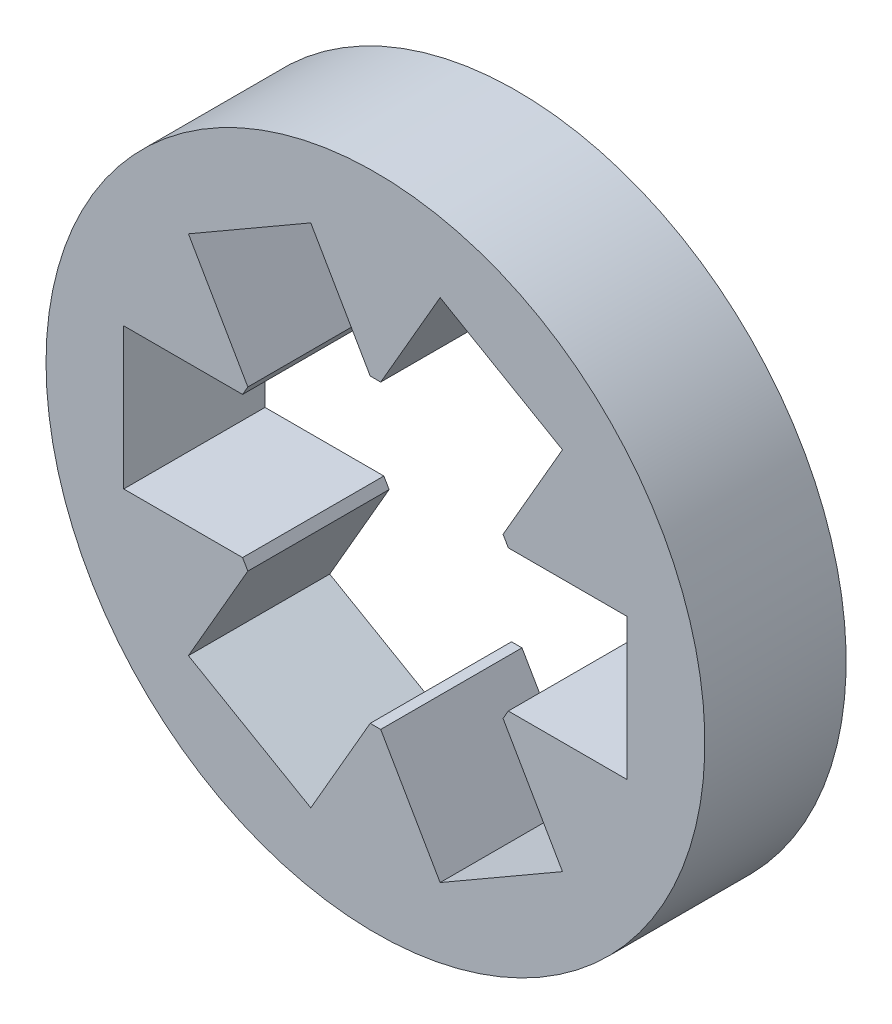
SolidWorks part; units mm, degrees
ref_plane "Front Plane" through (0, 0, 0) normal (0, 0, 1) x (1, 0, 0)
ref_plane "Top Plane" through (0, 0, 0) normal (0, 1, 0) x (1, 0, 0)
ref_plane "Right Plane" through (0, 0, 0) normal (1, 0, 0) x (0, 0, -1)
sketch "Sketch1" plane through (0, 0, 0) normal (0, 0, 1) x (1, 0, 0)
  line L0 (110.2077, 0) -> (110.2077, -1.524)
  line L1 (110.2077, -1.524) -> (108.9259, -1.524)
  line L2 (108.9259, -1.524) -> (108.8691, -1.6222)
  line L3 (108.8691, -1.6222) -> (109.51, -2.7323)
  line L4 (109.51, -2.7323) -> (108.1902, -3.4943)
  line L5 (108.1902, -3.4943) -> (107.5493, -2.3842)
  line L6 (107.5493, -2.3842) -> (107.4359, -2.3842)
  line L7 (107.4359, -2.3842) -> (106.795, -3.4943)
  line L8 (106.795, -3.4943) -> (105.4751, -2.7323)
  line L9 (105.4751, -2.7323) -> (106.116, -1.6222)
  line L10 (106.116, -1.6222) -> (106.0593, -1.524)
  line L11 (106.0593, -1.524) -> (104.7775, -1.524)
  line L12 (104.7775, -1.524) -> (104.7775, 0)
  line L13 (104.7775, 0) -> (106.0593, 0)
  line L14 (106.0593, 0) -> (106.116, 0.0982)
  line L15 (106.116, 0.0982) -> (105.4751, 1.2083)
  line L16 (105.4751, 1.2083) -> (106.795, 1.9703)
  line L17 (106.795, 1.9703) -> (107.4359, 0.8602)
  line L18 (107.4359, 0.8602) -> (107.5493, 0.8602)
  line L19 (107.5493, 0.8602) -> (108.1902, 1.9703)
  line L20 (108.1902, 1.9703) -> (109.51, 1.2083)
  line L21 (109.51, 1.2083) -> (108.8691, 0.0982)
  line L23 (108.8691, 0.0982) -> (108.9259, 0)
  line L24 (108.9259, 0) -> (110.2077, 0)
  circle A0 centre (107.4926, -0.762) radius 3.5535
extrude "Boss-Extrude1" add sketch "Sketch1" along normal blind 1.524
